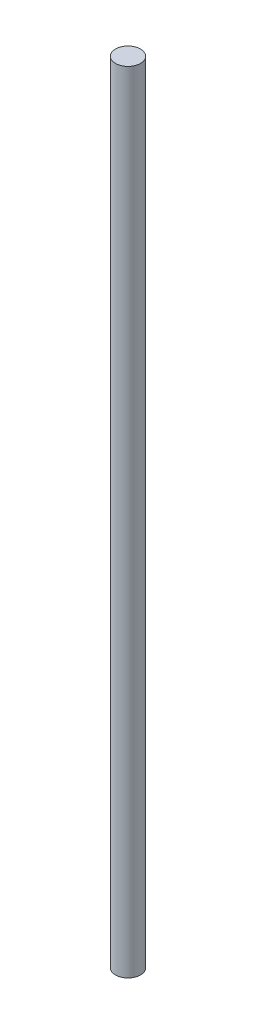
SolidWorks part; units mm, degrees
ref_plane "Front Plane" through (0, 0, 0) normal (0, 0, 1) x (1, 0, 0)
ref_plane "Top Plane" through (0, 0, 0) normal (0, 1, 0) x (1, 0, 0)
ref_plane "Right Plane" through (0, 0, 0) normal (1, 0, 0) x (0, 0, -1)
sketch "Sketch1" plane through (0, 0, 0) normal (0, 1, 0) x (1, 0, 0)
  circle A0 centre (0, 0) radius 2.5
  dimension "D1" = 5
extrude "Boss-Extrude1" add sketch "Sketch1" along normal offset from surface (158 mm away) 10
